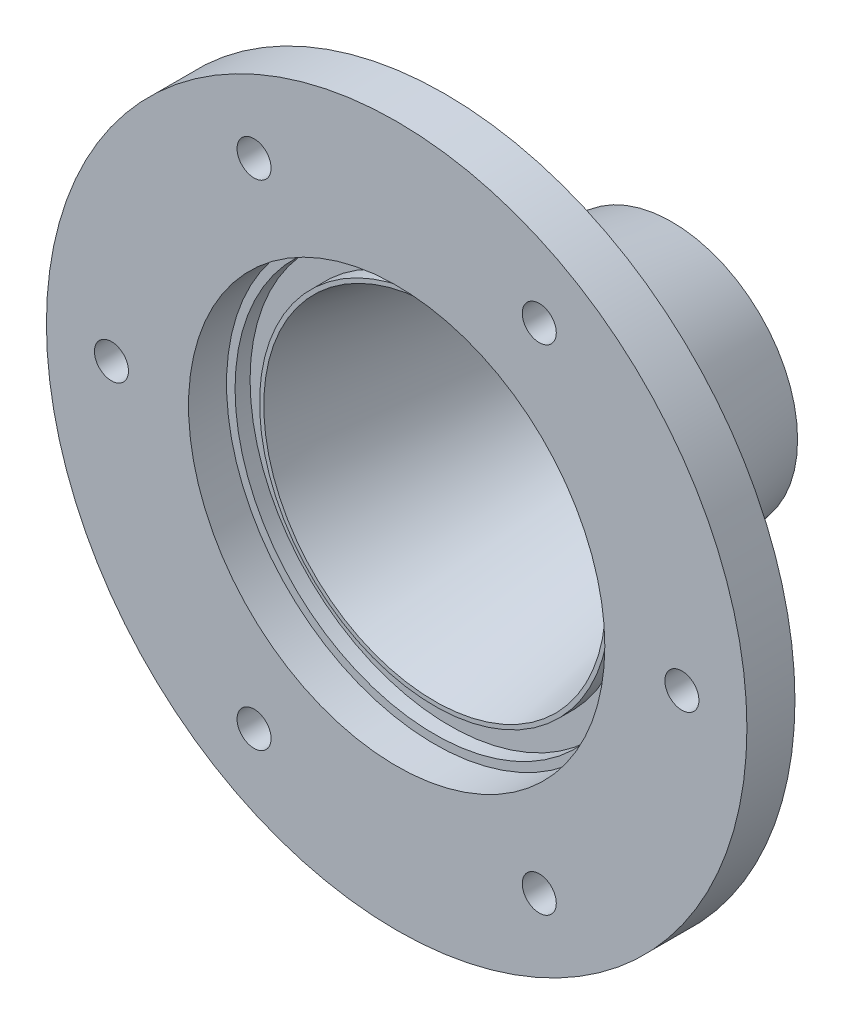
SolidWorks part; units mm, degrees
ref_plane "Front" through (0, 0, 0) normal (0, 0, 1) x (1, 0, 0)
ref_plane "Top" through (0, 0, 0) normal (0, 1, 0) x (1, 0, 0)
ref_plane "Right" through (0, 0, 0) normal (1, 0, 0) x (0, 0, -1)
sketch "Sketch1" plane through (0, 0, 0) normal (0, 0, 1) x (1, 0, 0)
  circle A0 centre (0, 0) radius 35
  dimension "D1" = 70
extrude "Boss-Extrude1" add sketch "Sketch1" against normal blind 6.8
sketch "Sketch2" plane through (0, 0, 0) normal (0, 0, 1) x (1, 0, 0)
  line L0 (-28.5, 0) -> (28.5, 0) construction
  circle A0 centre (0, 0) radius 28.5 construction
  point P5 (0, 0)
  dimension "D1" = 57
hole_wizard "M3 Clearance Hole1" positions "Sketch3" profile "Sketch4" hole size "M3" standard "ANSI Metric" end condition through all
sketch "Sketch3" plane through (0, 0, 0) normal (0, 0, 1) x (1, 0, 0)
  point P9 (-28.5, 0)
sketch "Sketch4" plane through (-28.5, 0, 0) normal (1, 0, 0) x (0, -1, 0)
  line L0 (0, 0) -> (0, 6.8)
  line L1 (0, 6.8) -> (1.7, 6.8)
  line L2 (1.7, 6.8) -> (1.7, 0)
  line L5 (1.7, 0) -> (0, 0)
  line L11 (0, -6.35) -> (0, 107.95) construction
  dimension "Thru Hole Dia." = 3.4
  dimension "Thru Hole Depth" = 6.8
pattern_circular "CirPattern1" count 6 over 360 about axis through (0, 0, 0) along (0, 0, 1) of "M3 Clearance Hole1"
sketch "Sketch5" plane through (0, 0, 0) normal (0, 0, 1) x (1, 0, 0)
  circle A0 centre (0, 0) radius 20.8
  dimension "D1" = 41.6
extrude "Cut-Extrude1" cut sketch "Sketch5" against normal blind 3.8
sketch "Sketch6" plane through (0, 0, -3.8) normal (0, 0, 1) x (1, 0, 0)
  circle A0 centre (0, 0) radius 19.95
  circle A1 centre (0, 0) radius 17.5
  dimension "D1" = 39.9
  dimension "D2" = 35
extrude "Cut-Extrude2" cut sketch "Sketch6" against normal blind 1.5
sketch "Sketch7" plane through (0, 0, -6.8) normal (0, 0, -1) x (-1, 0, 0)
  circle A0 centre (0, 0) radius 24.95
  circle A1 centre (0, 0) radius 42.8365
  dimension "D1" = 49.9
extrude "Cut-Extrude3" cut sketch "Sketch7" against normal blind 2
sketch "Sketch9" [suppressed] plane through (0, 0, -2) normal (0, 0, 1) x (1, 0, 0)
  circle A0 centre (0, 0) radius 17.5
  dimension "D1" = 35
extrude "Cut-Extrude4" [suppressed] cut sketch "Sketch9" against normal blind 35.24 draft 13.2 contours A0
sketch "Sketch11" plane through (0, 0, -6.8) normal (0, 0, 1) x (1, 0, 0)
  circle A0 centre (0, 0) radius 16.635
  dimension "D1" = 33.27
extrude "Boss-Extrude5" add sketch "Sketch11" against normal blind 20.7 draft 11.13
sketch "Sketch12" plane through (0, 0, -3.8) normal (0, 0, 1) x (1, 0, 0)
  circle A0 centre (0, 0) radius 17.08
  dimension "D1" = 34.16
extrude "Cut-Extrude5" cut sketch "Sketch12" against normal blind 28 draft 11.13
ref_plane "Plane1" through (0, 0, -35.24) normal (0, 0, 1) x (1, 0, 0)
sketch "Sketch14" plane through (0, 0, 0) normal (1, 0, 0) x (0, 0, -1)
  line L0 (35.24, 16.0946) -> (33.4334, -11.3953)
  line L1 (35.24, 38.5) -> (35.24, -38.5) construction
  line L2 (6.8, -16.635) -> (27.5, -12.5626) construction
  line L3 (33.4334, -11.3953) -> (27.5, -15.4745)
  line L4 (27.5, -15.4745) -> (27.5, 15.8753)
  line L5 (27.5, 15.8753) -> (35.24, 16.0946)
  line L8 (27.5, -12.4174) -> (27.5, 12.4174) construction
  line L9 (27.5, -12.5626) -> (27.5, 12.5626) construction
  dimension "D1" = 3.76
extrude "Cut-Extrude6" [suppressed] cut sketch "Sketch14" against normal through all both and the other way through all
